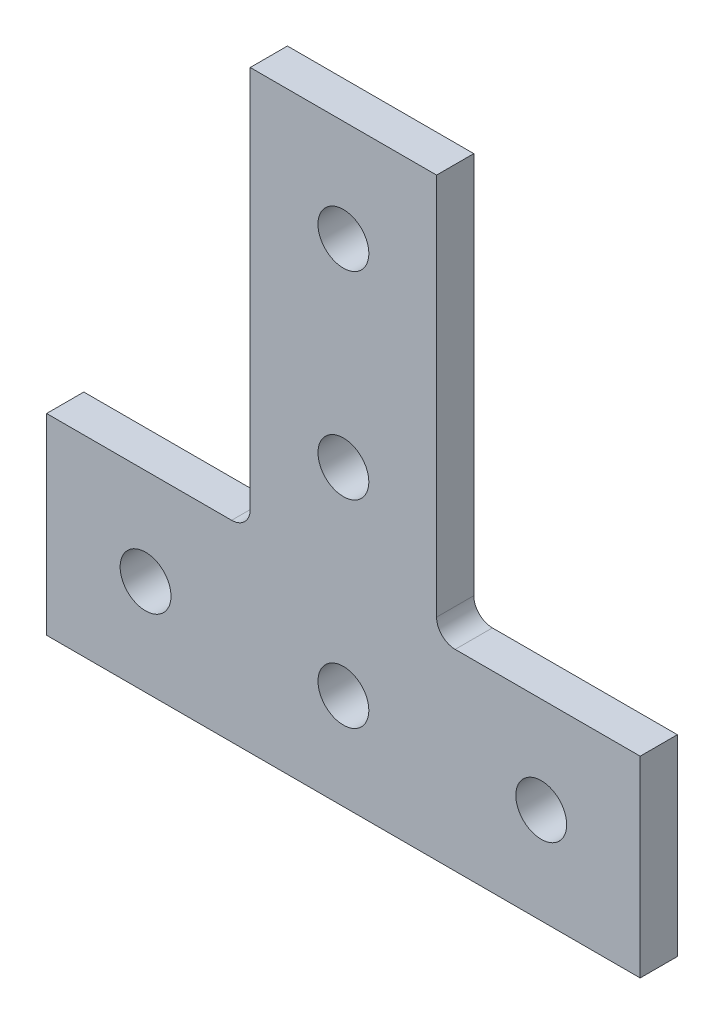
SolidWorks part; units mm, degrees
ref_plane "Front Plane" through (0, 0, 0) normal (0, 0, 1) x (1, 0, 0)
ref_plane "Top Plane" through (0, 0, 0) normal (0, 1, 0) x (1, 0, 0)
ref_plane "Right Plane" through (0, 0, 0) normal (1, 0, 0) x (0, 0, -1)
sketch "Sketch1" plane through (0, 0, 0) normal (0, 0, 1) x (1, 0, 0)
  line L0 (0, 38.1) -> (0, -38.1) construction
  line L1 (-38.1, -38.1) -> (38.1, -38.1) construction
  line L2 (38.1, -38.1) -> (38.1, -13.4366) construction
  line L3 (25.4, -22.5044) -> (25.4, -29.0322) construction
  line L4 (11.9634, 38.1) -> (-11.9634, 38.1) construction
  point P0 (0, -0.3683)
  point P4 (0, 0)
  point P8 (0, -38.1)
  point P11 (25.4, -25.7683)
  point P12 (38.1, -25.7683)
  point P15 (0, 38.1)
  dimension "Length" = 76.2
  dimension "Width1" = 24.6634
  dimension "Hole Dia" = 6.5278
  dimension "Hole to Edge" = 12.7
  dimension "Hole Spacing" = 25.4
  dimension "Width2" = 23.9268
sketch "Sketch2" plane through (0, 0, 0) normal (1, 0, 0) x (0, 0, -1)
  line L0 (2.3876, 0) -> (-2.3876, 0) construction
  point P4 (0, 0)
  dimension "Thickness" = 4.7752
sketch "Sketch3" plane through (0, 0, 0) normal (0, 0, 1) x (1, 0, 0)
  line L0 (38.1, -38.1) -> (-38.1, -38.1)
  line L1 (38.1, -38.1) -> (38.1, -13.4366)
  line L2 (38.1, -13.4366) -> (14.351, -13.4366)
  line L3 (11.9634, -11.049) -> (11.9634, 38.1)
  line L4 (11.9634, 38.1) -> (-11.9634, 38.1)
  line L5 (11.9634, 38.1) -> (-11.9634, 38.1) construction
  line L6 (-38.1, -38.1) -> (38.1, -38.1) construction
  line L7 (0, -38.1) -> (0, 38.1) construction
  line L8 (-11.9634, -11.049) -> (-11.9634, 38.1)
  line L9 (-38.1, -13.4366) -> (-14.351, -13.4366)
  line L10 (-38.1, -38.1) -> (-38.1, -13.4366)
  arc A0 (-11.9634, -11.049) -> (-14.351, -13.4366) centre (-14.351, -11.049) cw
  arc A1 (14.351, -13.4366) -> (11.9634, -11.049) centre (14.351, -11.049) cw
  point P20 (-11.9634, -13.4366)
  point P23 (11.9634, -13.4366)
  dimension "Radius" = 2.3876
extrude "Boss-Extrude1" add sketch "Sketch3" against normal up to vertex (2.3876 mm away) and the other way up to vertex (2.3876 mm away) up to point (0, 0, -2.3876) other way up to point (0, 0, 2.3876)
sketch "Sketch4" plane through (0, 0, 2.3876) normal (0, 0, 1) x (1, 0, 0)
  line L0 (25.4, -22.5044) -> (25.4, -29.0322) construction
  line L1 (0, 38.1) -> (0, -38.1) construction
  line L2 (0, -38.1) -> (0, 38.1) construction
  line L3 (-38.1, -38.1) -> (38.1, -38.1) construction
  line L4 (0, -0.3683) -> (-11.9634, -0.3683) construction
  line L5 (-11.9634, 38.1) -> (-11.9634, -11.049) construction
  circle A0 centre (25.4, -25.7683) radius 3.2639
  circle A1 centre (0, -25.7683) radius 3.2639
  circle A2 centre (-25.4, -25.7683) radius 3.2639
  circle A3 centre (0, -0.3683) radius 3.2639
  circle A4 centre (0, 25.0317) radius 3.2639
extrude "Cut-Extrude1" cut sketch "Sketch4" against normal through all
ref_plane "Plane1" through (0, 0, 0) normal (-1, 0, 0) x (0, 0, 1)
ref_plane "Plane2" through (0, -25.7683, 0) normal (0, 1, 0) x (1, 0, 0)
